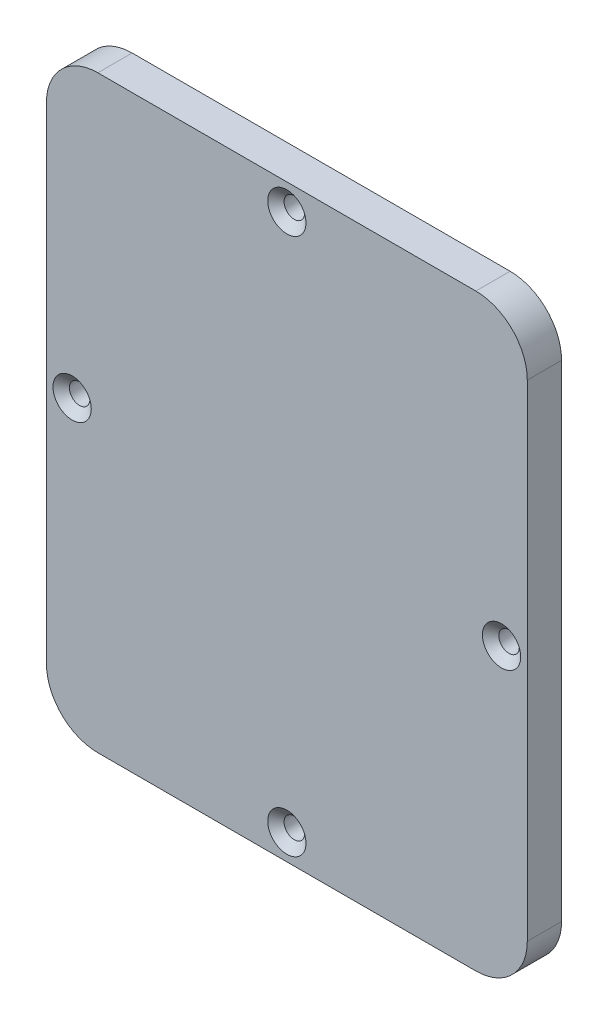
SolidWorks part; units mm, degrees
ref_plane "Front Plane" through (0, 0, 0) normal (0, 0, 1) x (1, 0, 0)
ref_plane "Top Plane" through (0, 0, 0) normal (0, 1, 0) x (1, 0, 0)
ref_plane "Right Plane" through (0, 0, 0) normal (1, 0, 0) x (0, 0, -1)
sketch "Sketch1" plane through (0, 0, 0) normal (0, 0, 1) x (1, 0, 0)
  line L8 (3.175, -6.35) -> (73.175, -6.35)
  line L9 (82.7, 3.175) -> (82.7, 93.175)
  line L10 (73.175, 102.7) -> (3.175, 102.7)
  line L11 (-6.35, 93.175) -> (-6.35, 3.175)
  arc A8 (-6.35, 3.175) -> (3.175, -6.35) centre (3.175, 3.175) ccw
  arc A9 (73.175, -6.35) -> (82.7, 3.175) centre (73.175, 3.175) ccw
  arc A10 (82.7, 93.175) -> (73.175, 102.7) centre (73.175, 93.175) ccw
  arc A11 (3.175, 102.7) -> (-6.35, 93.175) centre (3.175, 93.175) ccw
  circle A12 centre (38.175, -1.5875) radius 1.5875
  circle A13 centre (77.9375, 48.175) radius 1.5875
  circle A14 centre (38.175, 97.9375) radius 1.5875
  circle A15 centre (-1.5875, 48.175) radius 1.5875
extrude "Boss-Extrude1" add sketch "Sketch1" along normal blind 6.35
hole_wizard "CSK for #6 Flat Head Machine Screw (100)1" positions "Sketch2" profile "Sketch3" countersink size "#6" standard "ANSI Inch" end condition through all
sketch "Sketch2" plane through (0, 0, 6.35) normal (0, 0, 1) x (1, 0, 0)
  point P0 (-1.5875, 48.175)
  point P3 (77.9375, 48.175)
  point P6 (38.175, -1.5875)
  point P9 (38.175, 97.9004)
  point P14 (36.7152, 98.5613)
  point P15 (37.4665, 99.3581)
  point P16 (38.175, 97.9004)
sketch "Sketch3" plane through (-1.5875, 48.175, 6.35) normal (1, 0, 0) x (0, -1, 0)
  line L0 (0, 0) -> (0, 6.35)
  line L1 (0, 6.35) -> (1.8986, 6.35)
  line L2 (1.8986, 6.35) -> (1.8986, 1.38)
  line L3 (1.8986, 1.38) -> (3.5433, 0)
  line L5 (3.5433, 0) -> (0, 0)
  line L6 (-1.8987, 1.38) -> (-3.5433, 0) construction
  line L11 (0, -6.35) -> (0, 107.95) construction
  dimension "Thru Hole Dia." = 3.7973
  dimension "Thru Hole Depth" = 6.35
  dimension "Near C'Sink Dia." = 7.0866
  dimension "Near C'Sink Angle" = 100
